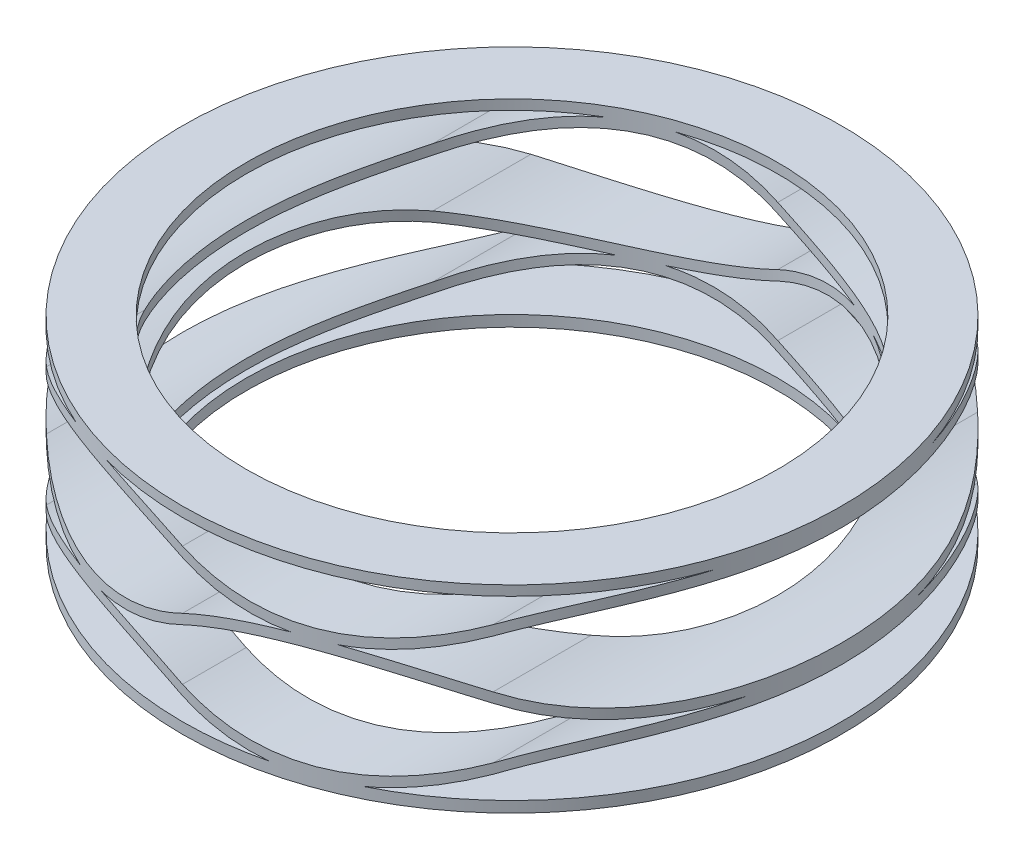
SolidWorks part; units mm, degrees
ref_plane "Front Plane" through (0, 0, 0) normal (0, 0, 1) x (1, 0, 0)
ref_plane "Top Plane" through (0, 0, 0) normal (0, 1, 0) x (1, 0, 0)
ref_plane "Right Plane" through (0, 0, 0) normal (1, 0, 0) x (0, 0, -1)
ref_plane "Plane1" through (0, 0, 0) normal (0, 1, 0) x (-1, 0, 0)
sketch "Sketch1" plane through (0, 0, 0) normal (0, 1, 0) x (-1, 0, 0)
  line L0 (15.494, -15.494) -> (15.494, 15.494)
  line L1 (15.494, 15.494) -> (-15.494, 15.494)
  line L2 (-15.494, 15.494) -> (-15.494, -15.494)
  line L3 (-15.494, -15.494) -> (15.494, -15.494)
extrude "Extrude1" add sketch "Sketch1" along normal blind 0.254
ref_plane "Plane2" through (0, 0, 0) normal (0, 0, 1) x (1, 0, 0)
sketch "Sketch2" plane through (0, 0, 0) normal (0, 0, 1) x (1, 0, 0)
  line L0 (10.3293, 0.7747) -> (10.3293, 1.0033)
  line L1 (-10.3293, 1.0033) -> (-10.3293, 0.7747)
  arc A0 (-10.3293, 0.7747) -> (-5.1647, 0.7747) centre (-7.747, 6.3231) ccw
  arc A1 (-5.1647, 0.7747) -> (0, 0.7747) centre (-2.5823, -4.2721) cw
  arc A2 (0, 0.7747) -> (5.1647, 0.7747) centre (2.5823, 6.3231) ccw
  arc A3 (5.1647, 0.7747) -> (10.3293, 0.7747) centre (7.747, -4.2721) cw
  arc A4 (10.3293, 1.0033) -> (5.1647, 1.0033) centre (7.747, -4.0435) ccw
  arc A5 (5.1647, 1.0033) -> (0, 1.0033) centre (2.5823, 6.5517) cw
  arc A6 (0, 1.0033) -> (-5.1647, 1.0033) centre (-2.5823, -4.0435) ccw
  arc A7 (-5.1647, 1.0033) -> (-10.3293, 1.0033) centre (-7.747, 6.5517) cw
extrude "Extrude2" add sketch "Sketch2" against normal blind 9.4513 and the other way blind 9.4513
ref_plane "Plane3" through (0, 0, 0) normal (0, 0, 1) x (1, 0, 0)
sketch "Sketch3" plane through (0, 0, 0) normal (0, 0, 1) x (1, 0, 0)
  line L0 (-10.3293, 2.4257) -> (-10.3293, 2.1971)
  line L1 (10.3293, 2.1971) -> (10.3293, 2.4257)
  arc A0 (-10.3293, 2.1971) -> (-5.1647, 2.1971) centre (-7.747, -3.3513) cw
  arc A1 (-5.1647, 2.1971) -> (0, 2.1971) centre (-2.5823, 7.4845) ccw
  arc A2 (0, 2.1971) -> (5.1647, 2.1971) centre (2.5823, -3.3513) cw
  arc A3 (5.1647, 2.1971) -> (10.3293, 2.1971) centre (7.747, 7.4845) ccw
  arc A4 (10.3293, 2.4257) -> (5.1647, 2.4257) centre (7.747, 7.7131) cw
  arc A5 (5.1647, 2.4257) -> (0, 2.4257) centre (2.5823, -3.1227) ccw
  arc A6 (0, 2.4257) -> (-5.1647, 2.4257) centre (-2.5823, 7.7131) cw
  arc A7 (-5.1647, 2.4257) -> (-10.3293, 2.4257) centre (-7.747, -3.1227) ccw
extrude "Extrude3" add sketch "Sketch3" against normal blind 9.2964 and the other way blind 9.2964
ref_plane "Plane4" through (0, 0, 0) normal (0, 0, 1) x (1, 0, 0)
sketch "Sketch4" plane through (0, 0, 0) normal (0, 0, 1) x (1, 0, 0)
  line L0 (10.3293, 3.5433) -> (10.3293, 3.7719)
  line L1 (-10.3293, 3.7719) -> (-10.3293, 3.5433)
  arc A0 (-10.3293, 3.5433) -> (-5.1647, 3.5433) centre (-7.747, 9.0917) ccw
  arc A1 (-5.1647, 3.5433) -> (0, 3.5433) centre (-2.5823, -1.7441) cw
  arc A2 (0, 3.5433) -> (5.1647, 3.5433) centre (2.5823, 9.0917) ccw
  arc A3 (5.1647, 3.5433) -> (10.3293, 3.5433) centre (7.747, -1.7441) cw
  arc A4 (10.3293, 3.7719) -> (5.1647, 3.7719) centre (7.747, -1.5155) ccw
  arc A5 (5.1647, 3.7719) -> (0, 3.7719) centre (2.5823, 9.3203) cw
  arc A6 (0, 3.7719) -> (-5.1647, 3.7719) centre (-2.5823, -1.5155) ccw
  arc A7 (-5.1647, 3.7719) -> (-10.3293, 3.7719) centre (-7.747, 9.3203) cw
extrude "Extrude4" add sketch "Sketch4" against normal blind 9.2964 and the other way blind 9.2964
ref_plane "Plane5" through (0, 4.3434, 0) normal (0, 1, 0) x (-1, 0, 0)
sketch "Sketch5" plane through (0, 4.3434, 0) normal (0, 1, 0) x (-1, 0, 0)
  line L0 (15.494, -15.494) -> (15.494, 15.494)
  line L1 (15.494, 15.494) -> (-15.494, 15.494)
  line L2 (-15.494, 15.494) -> (-15.494, -15.494)
  line L3 (-15.494, -15.494) -> (15.494, -15.494)
extrude "Extrude5" add sketch "Sketch5" along normal blind 0.2286
ref_plane "Plane6" through (0, 0, 0) normal (0, 1, 0) x (-1, 0, 0)
sketch "Sketch6" plane through (0, 0, 0) normal (0, 1, 0) x (-1, 0, 0)
  line L0 (15.494, -15.494) -> (15.494, 15.494)
  line L1 (15.494, 15.494) -> (-15.494, 15.494)
  line L2 (-15.494, 15.494) -> (-15.494, -15.494)
  line L3 (-15.494, -15.494) -> (15.494, -15.494)
  circle A0 centre (0, 0) radius 7.62
  dimension "D1" = 15.24
extrude "Extrude6" cut sketch "Sketch6" along normal blind 4.572
ref_plane "Plane7" through (0, 0, 0) normal (0, 1, 0) x (-1, 0, 0)
sketch "Sketch7" plane through (0, 0, 0) normal (0, 1, 0) x (-1, 0, 0)
  circle A0 centre (0, 0) radius 6.1468
  circle A1 centre (0, 0) radius 7.62 construction
  dimension "D1" = 1.4732
extrude "Extrude7" cut sketch "Sketch7" along normal blind 4.572
